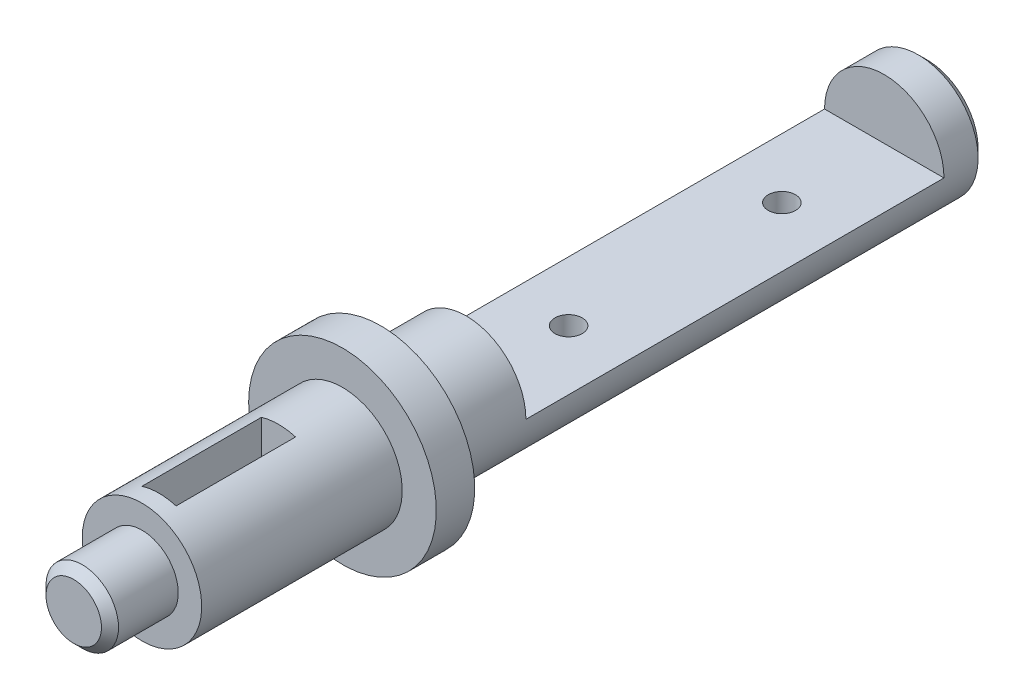
SolidWorks part; units mm, degrees
ref_plane "Front Plane" through (0, 0, 0) normal (0, 0, 1) x (1, 0, 0)
ref_plane "Top Plane" through (0, 0, 0) normal (0, 1, 0) x (1, 0, 0)
ref_plane "Right Plane" through (0, 0, 0) normal (1, 0, 0) x (0, 0, -1)
sketch "Sketch1" plane through (0, 0, 0) normal (0, 0, 1) x (1, 0, 0)
  circle A0 centre (0, 0) radius 4.25
  dimension "D1" = 8.5
extrude "Boss-Extrude1" add sketch "Sketch1" along normal blind 8
chamfer "Chamfer1" distance 1 angle 45 1 edges at (4.25, 0, 8)
sketch "Sketch2" plane through (0, 0, 0) normal (0, 0, -1) x (-1, 0, 0)
  circle A0 centre (0, 0) radius 7
  dimension "D1" = 14
extrude "Boss-Extrude2" add sketch "Sketch2" along normal blind 23.5
sketch "Sketch4" plane through (0, 0, -23.5) normal (0, 0, -1) x (-1, 0, 0)
  circle A0 centre (0, 0) radius 11
  dimension "D1" = 22
extrude "Boss-Extrude3" add sketch "Sketch4" along normal blind 4.5
sketch "Sketch5" plane through (0, 0, -28) normal (0, 0, -1) x (-1, 0, 0)
  circle A0 centre (0, 0) radius 7
  dimension "D1" = 14
extrude "Boss-Extrude4" add sketch "Sketch5" along normal blind 64
sketch "Sketch6" plane through (0, 0, 0) normal (1, 0, 0) x (0, 0, -1)
  line L0 (92, -7) -> (92, 7) construction
  line L1 (87, 0) -> (38, 0)
  line L2 (87, 0) -> (87, 7)
  line L3 (87, 7) -> (38, 7)
  line L4 (38, 0) -> (38, 7)
  line L5 (87, 0) -> (38, 7) construction
  line L6 (87, 7) -> (38, 0) construction
  point P0 (62.5, 3.5)
  dimension "D1" = 5
  dimension "D2" = 49
  dimension "D3" = 7
extrude "Cut-Extrude2" cut sketch "Sketch6" against normal through all both and the other way through all
sketch "Sketch7" plane through (0, 0, 0) normal (0, 1, 0) x (1, 0, 0)
  line L0 (-7, 38) -> (7, 38) construction
  circle A0 centre (0, 75) radius 1.6
  circle A1 centre (0, 50) radius 1.6
  dimension "D1" = 3.2
  dimension "D2" = 25
  dimension "D3" = 12
extrude "Cut-Extrude3" cut sketch "Sketch7" against normal up to next
chamfer "Chamfer2" distance 1 angle 45 1 edges at (-7, 0, -92)
sketch "Sketch8" plane through (0, 0, 0) normal (0, 1, 0) x (1, 0, 0)
  line L1 (-2, 2) -> (2, 2)
  line L2 (-2, 2) -> (-2, 16)
  line L3 (-2, 16) -> (2, 16)
  line L4 (2, 2) -> (2, 16)
  line L5 (-2, 2) -> (2, 16) construction
  line L6 (-2, 16) -> (2, 2) construction
  line L7 (-3.25, -8) -> (3.25, -8) construction
  point P0 (0, 9)
  point P9 (0, 2)
  dimension "D1" = 14
  dimension "D2" = 10
  dimension "D3" = 4
extrude "Cut-Extrude4" cut sketch "Sketch8" along normal blind 10
